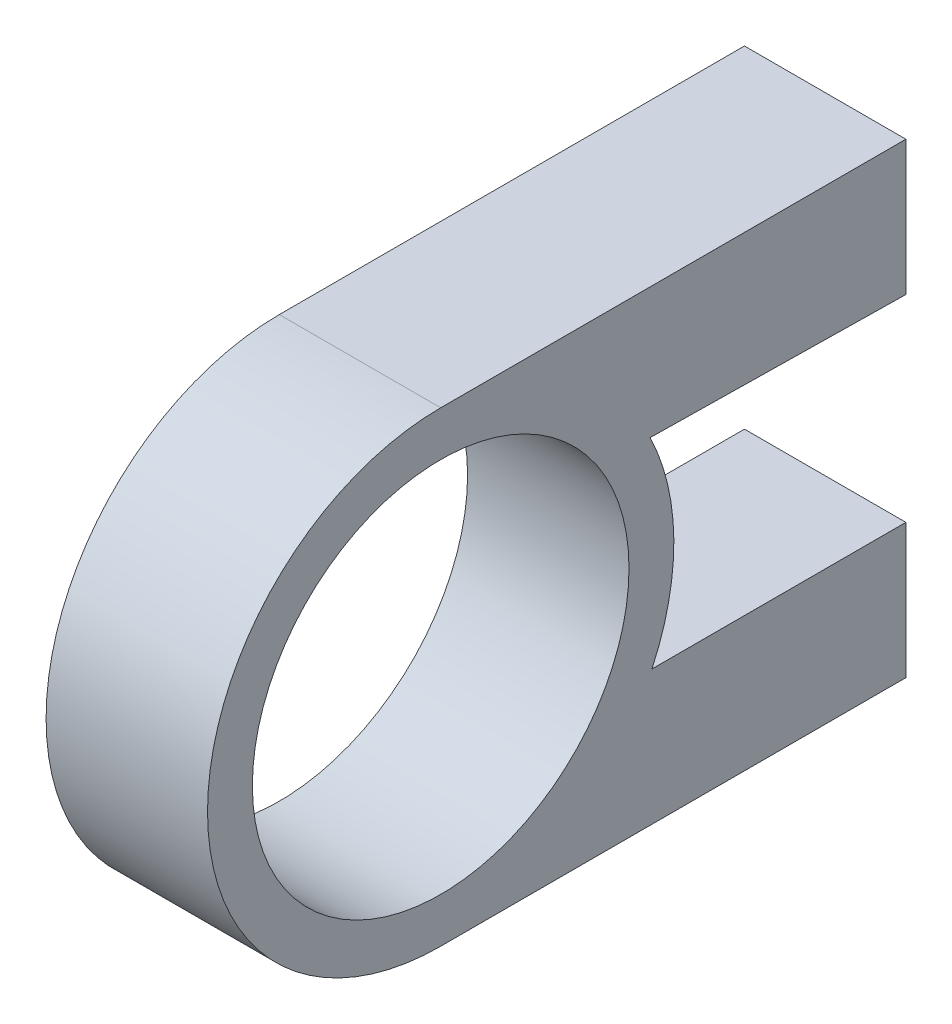
SolidWorks part; units mm, degrees
ref_plane "Front Plane" through (0, 0, 0) normal (1, 0, 0) x (0, 1, 0)
ref_plane "Top Plane" through (0, 0, 0) normal (0, 0, 1) x (0, 1, 0)
ref_plane "Right Plane" through (0, 0, 0) normal (0, 1, 0) x (-1, 0, 0)
sketch "Sketch1" plane through (0, 0, 0) normal (1, 0, 0) x (0, 1, 0)
  line L0 (-2.6, -2.1) -> (2.6, -2.1) construction
  line L2 (-2.6, 0) -> (-2.6, -5.1875)
  line L3 (-2.6, -5.1875) -> (-1.1, -5.1875)
  line L4 (2.6, 0) -> (2.6, -5.1875)
  line L5 (0, -2.1) -> (0, -5.0875) construction
  line L6 (-1.1, -2.3558) -> (-1.1, -5.1875)
  line L8 (1.144, -2.3348) -> (1.1, -5.1875)
  line L9 (1.1, -5.1875) -> (2.6, -5.1875)
  circle A0 centre (0, 0) radius 2.1
  arc A1 (-1.1, -2.3558) -> (1.144, -2.3348) centre (0, 0) ccw
  arc A2 (2.6, 0) -> (-2.6, 0) centre (0, 0) ccw
  dimension "D1" = 4.2
  dimension "D2" = 5.2
  dimension "D3" = 3.0875
  dimension "D4" = 1.1
extrude "Boss-Extrude2" add sketch "Sketch1" along normal blind 1.8
